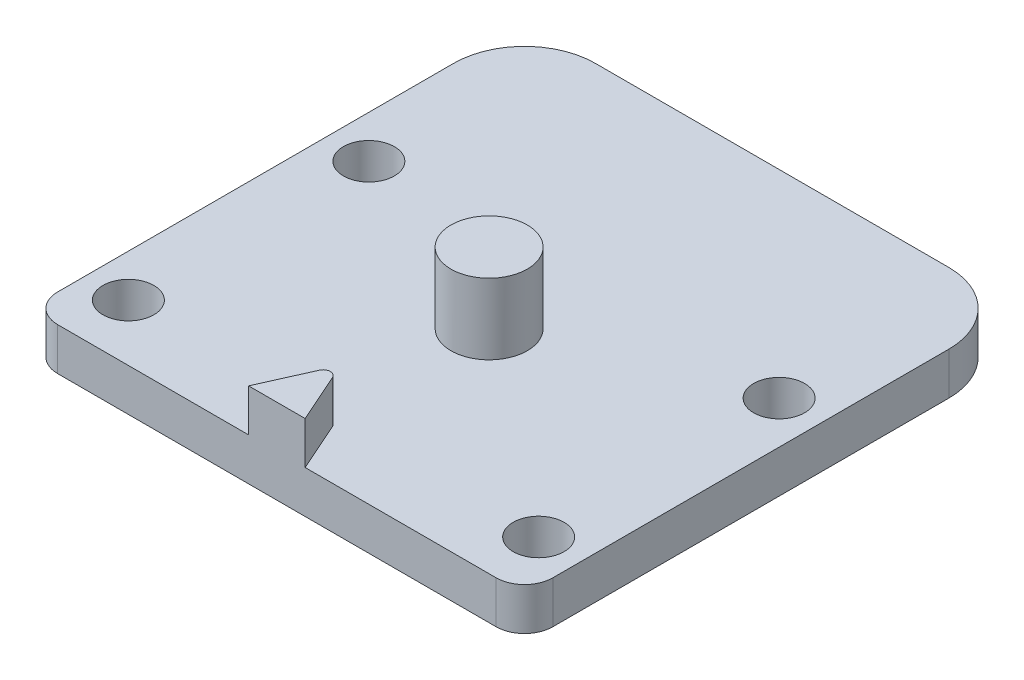
SolidWorks part; units mm, degrees
ref_plane "Front Plane" through (0, 0, 0) normal (0, 0, 1) x (1, 0, 0)
ref_plane "Top Plane" through (0, 0, 0) normal (0, 1, 0) x (1, 0, 0)
ref_plane "Right Plane" through (0, 0, 0) normal (1, 0, 0) x (0, 0, -1)
sketch "Sketch1" plane through (0, 0, 0) normal (0, 1, 0) x (1, 0, 0)
  line L1 (0, 0) -> (35, 0)
  line L2 (0, 0) -> (0, 35)
  line L3 (0, 35) -> (35, 35)
  line L4 (35, 0) -> (35, 35)
  point P5 (0, 0)
extrude "Boss-Extrude1" add sketch "Sketch1" along normal blind 3
sketch "Sketch2" plane through (0, 3, 0) normal (0, 1, 0) x (1, 0, 0)
  circle A0 centre (17.5, 15) radius 2.7
sketch "Sketch3" plane through (0, 3, 0) normal (0, 1, 0) x (1, 0, 0)
  circle A0 centre (3, 21) radius 1.8
extrude "Cut-Extrude2" cut sketch "Sketch3" against normal blind 3
ref_plane "Plane1" through (17.5, 0, 0) normal (1, 0, 0) x (0, 0, -1)
ref_plane "Plane2" through (0, 0, -12.5) normal (0, 0, 1) x (1, 0, 0)
mirror "Mirror1" about plane through (0, 0, -12.5) normal (0, 0, 1) of "Cut-Extrude2"
mirror "Mirror2" about plane through (17.5, 0, 0) normal (1, 0, 0) of "Mirror1", "Cut-Extrude2"
extrude "Boss-Extrude2" add sketch "Sketch2" along normal blind 5 contours A0
sketch "Sketch5" plane through (0, 3, 0) normal (0, 1, 0) x (1, 0, 0)
  line L0 (17.5, 15) -> (17.5, 0) construction
  line L1 (17.5, 4.5) -> (15.5, 0)
  line L2 (15.5, 0) -> (19.5, 0)
  line L3 (19.5, 0) -> (17.5, 4.5)
extrude "Boss-Extrude3" add sketch "Sketch5" along normal blind 3
fillet "Fillet2" radius 0.5 1 edges at (17.5, 4.5, -4.5)
fillet "Fillet3" radius 2 2 edges at (35, 1.5, 0) (0, 1.5, 0)
fillet "Fillet4" radius 5 2 edges at (0, 1.5, -35) (35, 1.5, -35)
